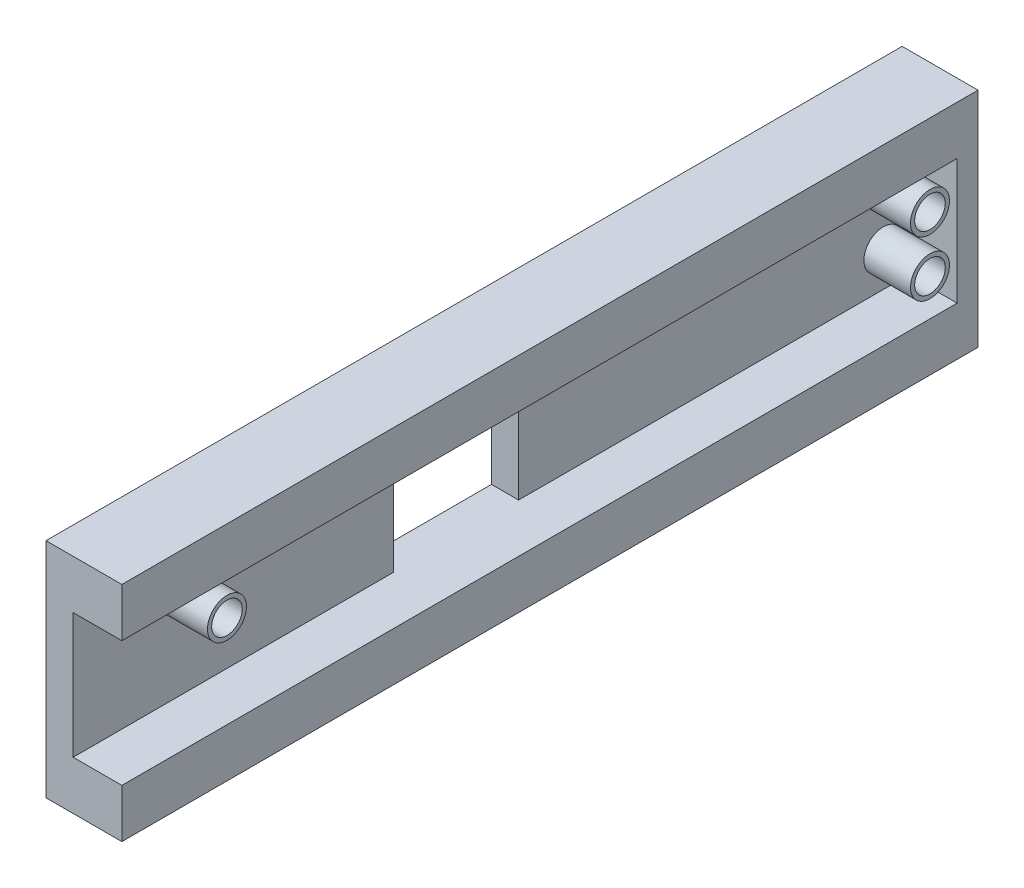
SolidWorks part; units mm, degrees
other "Markup1"
sketch "Sketch16" plane through (0, -7, 30.75) normal (0.1219, -0.0208, 0.9923) x (0.9703, -0.2078, -0.1236)
other "Markup2"
sketch "Sketch17" plane through (-5.45, 7, -30.75) normal (-0.9792, 0.0018, -0.2028) x (-0.2028, 0.0186, 0.9791)
ref_plane "Front Plane" through (0, 0, 0) normal (0, 0, 1) x (1, 0, 0)
ref_plane "Top Plane" through (0, 0, 0) normal (0, 1, 0) x (1, 0, 0)
ref_plane "Right Plane" through (0, 0, 0) normal (1, 0, 0) x (0, 0, -1)
sketch "Sketch9" plane through (0, 0, 0) normal (0, 1, 0) x (1, 0, 0)
  line L0 (0, 22.5148) -> (0, -30.75) construction
  line L1 (-5.45, 30.75) -> (-5.45, -30.75) construction
  line L2 (-32.9016, 0) -> (0, 0) construction
  line L3 (0, -30.75) -> (-5.45, -30.75)
  line L4 (-5.45, -30.75) -> (-5.45, 30.75)
  line L6 (0, 30.75) -> (-5.45, 30.75)
  line L7 (0, 30.75) -> (0, -30.75)
  point P7 (-5.45, 0)
  dimension "D1" = 61.5
  dimension "D2" = 5.45
extrude "Boss-Extrude3" add sketch "Sketch9" along normal mid plane 16
sketch "Sketch11" plane through (0, 0, 30.75) normal (0, 0, 1) x (1, 0, 0)
  line L0 (0, 3.2113) -> (0, -2.499) construction
  line L1 (0, 8) -> (0, -8) construction
  line L3 (0, -4.5) -> (-3.5, -4.5)
  line L4 (0, -4.5) -> (0, 4.5)
  line L5 (0, 4.5) -> (-3.5, 4.5)
  line L6 (-3.5, -4.5) -> (-3.5, 4.5)
  line L7 (0, -4.5) -> (-3.5, 4.5) construction
  line L8 (0, 4.5) -> (-3.5, -4.5) construction
  point P8 (-1.75, 0)
  dimension "D1" = 3.5
  dimension "D2" = 9
extrude "Cut-Extrude1" cut sketch "Sketch11" against normal through all
sketch "Sketch12" plane through (-5.45, 0, 0) normal (-1, 0, 0) x (0, 0, 1)
  line L0 (-30.75, 8) -> (-30.75, -8) construction
  line L7 (30.75, 0) -> (-30.75, 0) construction
  line L8 (30.75, 8) -> (30.75, -8) construction
  circle A0 centre (-27.45, 2) radius 1.4
  circle A1 centre (-27.45, -2) radius 1.4
  circle A2 centre (23.05, 2) radius 1.4
  dimension "D5" = 7.7
  dimension "D6" = 50.5
  dimension "D7" = 2.8
  dimension "D1" = 2
extrude "Boss-Extrude4" add sketch "Sketch12" against normal blind 5.3
sketch "Sketch13" plane through (-0.15, 0, 0) normal (1, 0, 0) x (0, 0, -1)
  circle A0 centre (-23.05, 2) radius 1.1
  circle A1 centre (27.45, 2) radius 1.1
  circle A2 centre (27.45, -2) radius 1.1
  dimension "D1" = 2.2
extrude "Cut-Extrude2" cut sketch "Sketch13" against normal through all
sketch "Sketch14" plane through (0, 0, -30.75) normal (0, 0, -1) x (-1, 0, 0)
  line L0 (0, -8) -> (5.45, -8) construction
  line L1 (0, 8) -> (4.5293, 8)
  line L2 (0, 8) -> (0, -8)
  line L3 (0, -8) -> (4.5293, -8)
  line L4 (4.5293, 8) -> (4.5293, -8)
  line L5 (0, 8) -> (4.5293, -8) construction
  line L6 (0, -8) -> (4.5293, 8) construction
  point P4 (2.2646, 0)
extrude "Boss-Extrude5" add sketch "Sketch14" against normal blind 1.5
sketch "Sketch15" plane through (-5.45, 0, 0) normal (-1, 0, 0) x (0, 0, 1)
  line L0 (30.75, 8) -> (30.75, -8) construction
  line L1 (-1.25, 4.5) -> (7.75, 4.5)
  line L2 (-1.25, 4.5) -> (-1.25, -4.5)
  line L3 (-1.25, -4.5) -> (7.75, -4.5)
  line L4 (7.75, 4.5) -> (7.75, -4.5)
  line L5 (-1.25, 4.5) -> (7.75, -4.5) construction
  line L6 (-1.25, -4.5) -> (7.75, 4.5) construction
  point P0 (3.25, 0)
  dimension "D1" = 9
  dimension "D2" = 9
  dimension "D3" = 27.5
extrude "Cut-Extrude3" cut sketch "Sketch15" against normal through all
